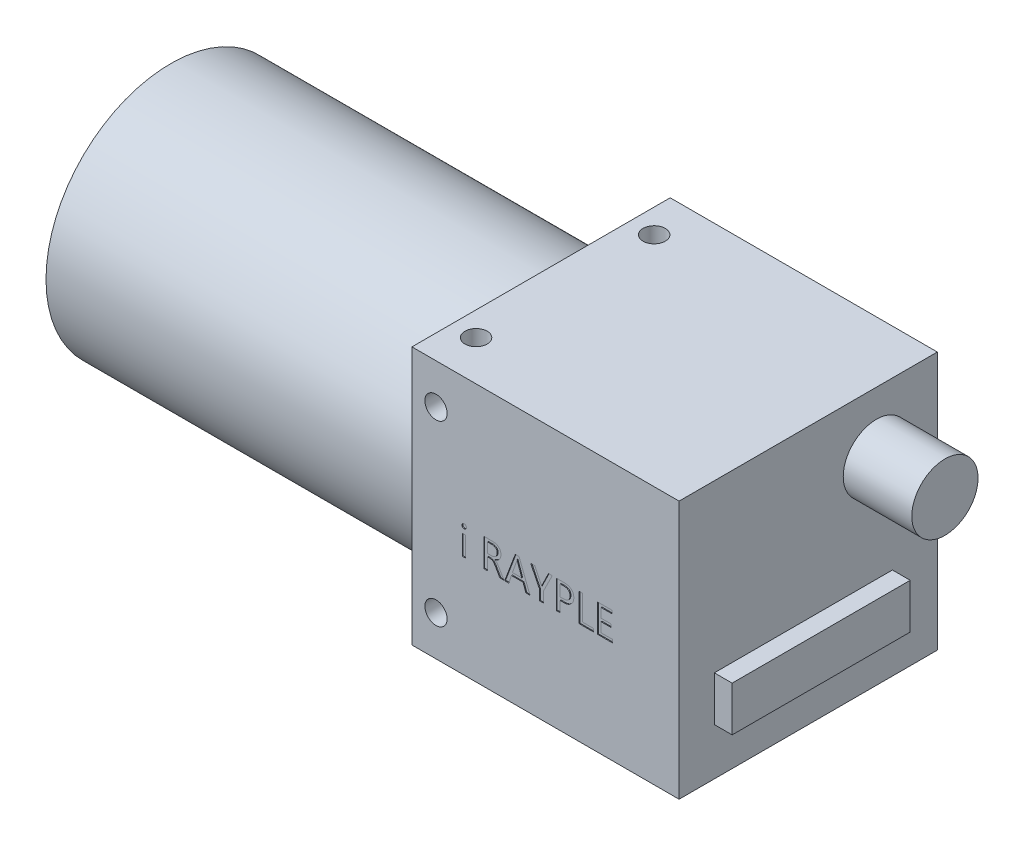
SolidWorks part; units mm, degrees
ref_plane "前视基准面" through (0, 0, 0) normal (0, 0, 1) x (1, 0, 0)
ref_plane "上视基准面" through (0, 0, 0) normal (0, 1, 0) x (1, 0, 0)
ref_plane "右视基准面" through (0, 0, 0) normal (1, 0, 0) x (0, 0, -1)
other "Configuration Table"
sketch "Sketch1" plane through (0, 0, 0) normal (0, 0, 1) x (1, 0, 0)
  line L1 (-15, -14.5) -> (15, -14.5)
  line L2 (-15, -14.5) -> (-15, 14.5)
  line L3 (-15, 14.5) -> (15, 14.5)
  line L4 (15, -14.5) -> (15, 14.5)
  line L5 (-15, -14.5) -> (15, 14.5) construction
  line L6 (-15, 14.5) -> (15, -14.5) construction
  point P0 (0, 0)
  dimension "D1" = 30
  dimension "D2" = 29
extrude "Boss-Extrude1" add sketch "Sketch1" along normal mid plane 29
sketch "Sketch4" plane through (-15, 0, 0) normal (-1, 0, 0) x (0, 0, 1)
  circle A1 centre (0, 0) radius 14
  dimension "D1" = 28
extrude "Boss-Extrude2" add sketch "Sketch4" along normal blind 41.6
sketch "Sketch5" plane through (15, 0, 0) normal (1, 0, 0) x (0, 0, -1)
  line L0 (0, 0) -> (14.5, 14.5) construction
  circle A0 centre (7.6557, 7.6557) radius 3.7215
  point P2 (0, 0)
extrude "Boss-Extrude3" add sketch "Sketch5" along normal blind 7.7
sketch "Sketch6" plane through (15, 0, 0) normal (1, 0, 0) x (0, 0, -1)
  line L0 (-14.5, -14.5) -> (14.5, -14.5) construction
  line L1 (-10.541, -9.2179) -> (9.459, -9.2179)
  line L2 (-10.541, -9.2179) -> (-10.541, -4.1821)
  line L3 (-10.541, -4.1821) -> (9.459, -4.1821)
  line L4 (9.459, -9.2179) -> (9.459, -4.1821)
  line L5 (-10.541, -9.2179) -> (9.459, -4.1821) construction
  line L6 (-10.541, -4.1821) -> (9.459, -9.2179) construction
  point P0 (-0.541, -6.7)
  dimension "D1" = 20
  dimension "D2" = 7.8
extrude "Boss-Extrude4" add sketch "Sketch6" along normal blind 2
sketch "Sketch7" plane through (0, 0, 14.5) normal (0, 0, 1) x (1, 0, 0)
  line L0 (-15, 14.5) -> (-15, -14.5) construction
  circle A0 centre (-12.3, 10) radius 1.25
  circle A1 centre (-12.3, -10) radius 1.25
  point P4 (0, 0)
  dimension "D1" = 2.5
  dimension "D2" = 20
  dimension "D3" = 10
  dimension "D4" = 2.7
extrude "Cut-Extrude1" cut sketch "Sketch7" against normal through all
sketch "Sketch8" plane through (0, 14.5, 0) normal (0, 1, 0) x (1, 0, 0)
  line L0 (-15, 14) -> (-15, -14) construction
  circle A0 centre (-12.3, 10) radius 1.25
  circle A1 centre (-12.3, -10) radius 1.25
  point P4 (0, 0)
  dimension "D1" = 2.5
  dimension "D2" = 20
  dimension "D3" = 10
  dimension "D4" = 2.7
extrude "Cut-Extrude2" cut sketch "Sketch8" against normal blind 3.5
sketch "Sketch9" plane through (0, -14.5, 0) normal (0, -1, 0) x (1, 0, 0)
  line L0 (-15, 14.5) -> (-15, -14.5) construction
  line L5 (-11, -6) -> (11, -6) construction
  line L6 (-11, -6) -> (-11, 6) construction
  line L7 (-11, 6) -> (11, 6) construction
  line L8 (11, -6) -> (11, 6) construction
  line L9 (-11, -6) -> (11, 6) construction
  line L10 (-11, 6) -> (11, -6) construction
  circle A0 centre (-11, 6) radius 0.75
  circle A1 centre (-11, -6) radius 0.75
  circle A2 centre (11, -6) radius 0.75
  circle A3 centre (11, 6) radius 0.75
  circle A4 centre (11, 0) radius 1.25
  circle A5 centre (-12.3, 10) radius 1.25
  circle A6 centre (-12.3, -10) radius 1.25
  point P0 (0, 0)
  point P16 (0, 0)
  dimension "D3" = 1.5
  dimension "D4" = 2.5
  dimension "D8" = 2.5
  dimension "D1" = 22
  dimension "D2" = 12
  dimension "D5" = 2.7
  dimension "D6" = 20
  dimension "D7" = 10
extrude "Cut-Extrude3" cut sketch "Sketch9" against normal blind 3.5
sketch "Sketch10" plane through (0, 0, 14.5) normal (0, 0, 1) x (1, 0, 0)
  line L0 (-9.6974, -3.0357) -> (8.9262, -3.0357) construction
  text T0 "i RAYPLE" font "微软雅黑" height in points 11
extrude "Cut-Extrude4" cut sketch "Sketch10" against normal blind 0.1
